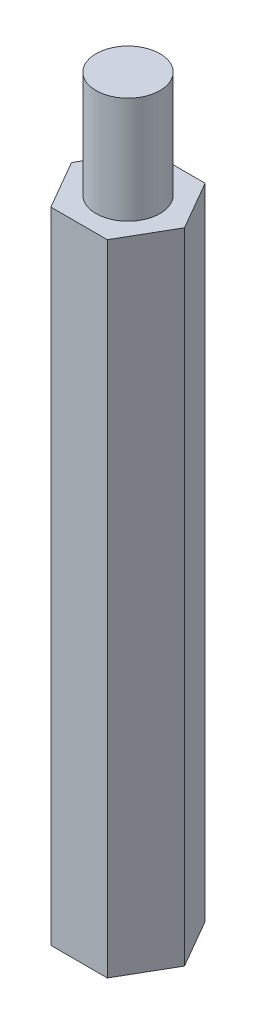
SolidWorks part; units mm, degrees
ref_plane "Front Plane" through (0, 0, 0) normal (0, 0, 1) x (1, 0, 0)
ref_plane "Top Plane" through (0, 0, 0) normal (0, 1, 0) x (1, 0, 0)
ref_plane "Right Plane" through (0, 0, 0) normal (1, 0, 0) x (0, 0, -1)
sketch "Sketch1" plane through (0, 0, 0) normal (0, 1, 0) x (1, 0, 0)
  line L1 (2.65, 0) -> (1.325, 2.295)
  line L2 (1.325, 2.295) -> (-1.325, 2.295)
  line L3 (-1.325, 2.295) -> (-2.65, 0)
  line L4 (-2.65, 0) -> (-1.325, -2.295)
  line L5 (-1.325, -2.295) -> (1.325, -2.295)
  line L6 (1.325, -2.295) -> (2.65, 0)
  circle A0 centre (0, 0) radius 2.295 construction
  dimension "D1" = 5.3
extrude "Boss-Extrude1" add sketch "Sketch1" along normal blind 30
sketch "Sketch2" plane through (0, 0, 0) normal (0, -1, 0) x (1, 0, 0)
  circle A0 centre (0, 0) radius 1.6
  dimension "D1" = 3.2
extrude "Cut-Extrude1" cut sketch "Sketch2" against normal blind 5
sketch "Sketch3" plane through (0, 30, 0) normal (0, 1, 0) x (1, 0, 0)
  circle A0 centre (0, 0) radius 1.5
  dimension "D1" = 3
extrude "Boss-Extrude3" add sketch "Sketch3" along normal blind 5
